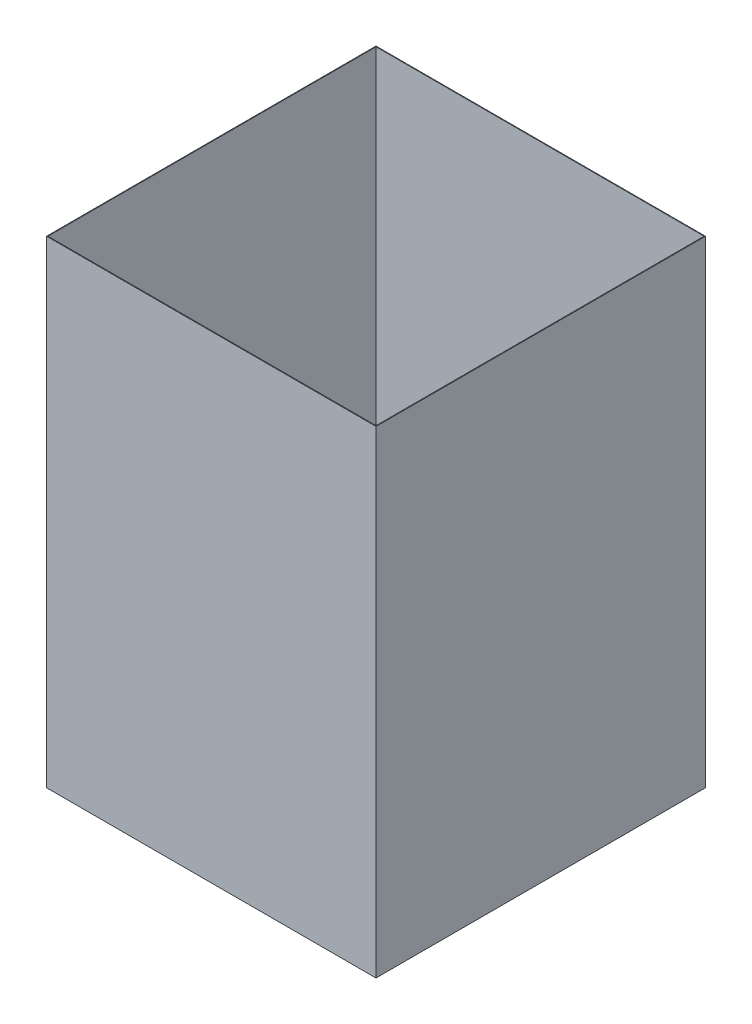
SolidWorks part; units mm, degrees
ref_plane "Front Plane" through (0, 0, 0) normal (0, 0, 1) x (1, 0, 0)
ref_plane "Top Plane" through (0, 0, 0) normal (0, 1, 0) x (1, 0, 0)
ref_plane "Right Plane" through (0, 0, 0) normal (1, 0, 0) x (0, 0, -1)
sketch "Sketch1" plane through (0, 0, 0) normal (0, 1, 0) x (1, 0, 0)
  line L1 (-100, 100) -> (100, 100)
  line L2 (-100, 100) -> (-100, -100)
  line L3 (-100, -100) -> (100, -100)
  line L4 (100, 100) -> (100, -100)
  line L5 (-100, 100) -> (100, -100) construction
  line L6 (-100, -100) -> (100, 100) construction
  point P0 (0, 0)
  point P6 (0, 100)
  point P7 (0, -100)
  point P8 (100, 0)
  point P9 (-100, 0)
  dimension "D1" = 200
  dimension "D2" = 200
extrude "Boss-Extrude1" add sketch "Sketch1" along normal blind 290
shell "Shell1" thickness 0.4
